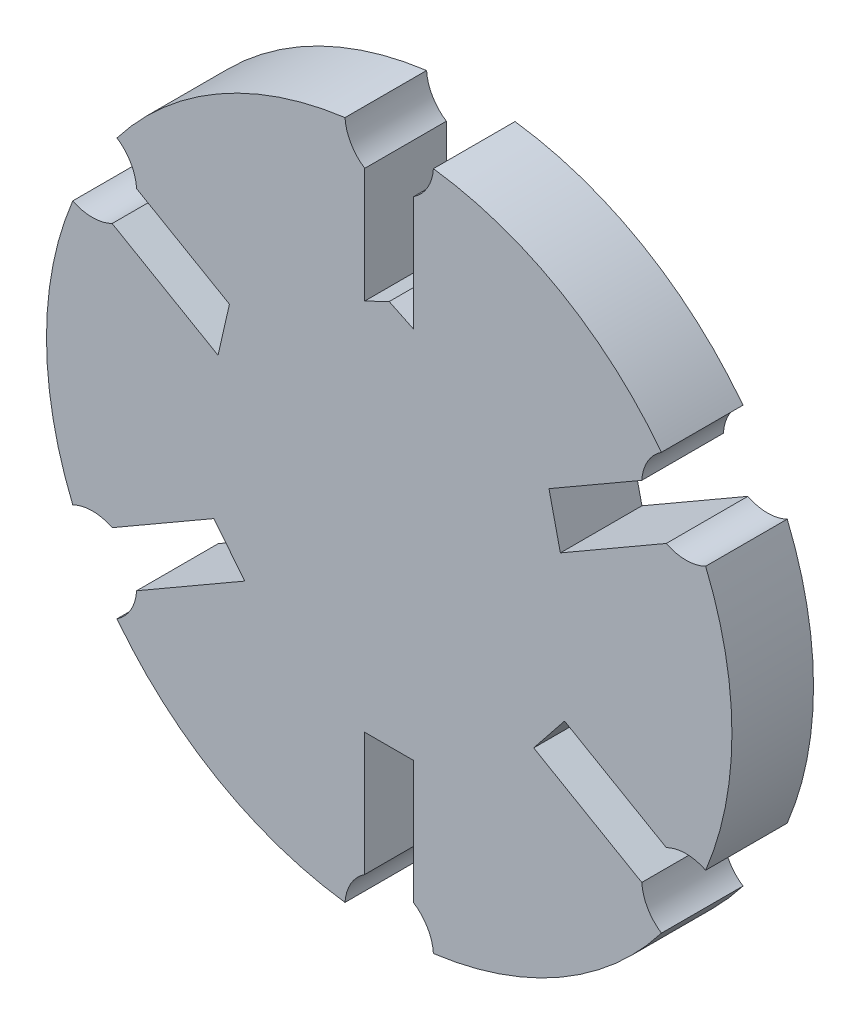
SolidWorks part; units mm, degrees
ref_plane "Front Plane" through (0, 0, 0) normal (0, 0, 1) x (1, 0, 0)
ref_plane "Top Plane" through (0, 0, 0) normal (0, 1, 0) x (1, 0, 0)
ref_plane "Right Plane" through (0, 0, 0) normal (1, 0, 0) x (0, 0, -1)
sketch "Sketch1" plane through (0, 0, 0) normal (0, 0, 1) x (1, 0, 0)
  line L1 (0, -1000) -> (0, -45) construction
  line L2 (19.4194, 15.4865) -> (0, 24.8383)
  line L3 (0, 24.8383) -> (-19.4194, 15.4865)
  line L4 (-19.4194, 15.4865) -> (-24.2156, -5.5271)
  line L5 (-24.2156, -5.5271) -> (-10.777, -22.3786)
  line L6 (-10.777, -22.3786) -> (10.777, -22.3786)
  line L7 (10.777, -22.3786) -> (24.2156, -5.5271)
  line L8 (24.2156, -5.5271) -> (19.4194, 15.4865)
  line L23 (22.9541, 0) -> (49000, 0) construction
  line L26 (20.9801, 8.6487) -> (33.9601, 16.1427)
  line L27 (19.5829, 14.7703) -> (30.9601, 21.3389)
  line L28 (3, 23.3936) -> (3, 37.4816)
  line L29 (-3, 23.3936) -> (-3, 37.4816)
  line L30 (-19.5829, 14.7703) -> (-30.9601, 21.3389)
  line L31 (-20.9801, 8.6487) -> (-33.9601, 16.1427)
  line L32 (-21.4909, -8.9437) -> (-33.9601, -16.1427)
  line L35 (-17.7055, -13.6864) -> (-30.9601, -21.3389)
  line L37 (17.7055, -13.6864) -> (30.9601, -21.3389)
  line L40 (21.4909, -8.9437) -> (33.9601, -16.1427)
  line L41 (-3, -22.3786) -> (-3, -37.4816)
  line L42 (3, -22.3786) -> (3, -37.4816)
  arc A0 (-5.4197, 41.6579) -> (-33.3669, 25.5225) centre (0, 0) ccw
  circle A1 centre (0, 0) radius 22.3786 construction
  circle A2 centre (0, 0) radius 45
  arc A3 (-5.4197, 41.6579) -> (5.4197, 41.6579) centre (0, 42.0089) ccw
  arc A4 (33.3669, 25.5225) -> (38.7866, 16.1353) centre (36.3808, 21.0045) ccw
  arc A5 (38.7866, -16.1353) -> (33.3669, -25.5225) centre (36.3808, -21.0045) ccw
  arc A6 (5.4197, -41.6579) -> (-5.4197, -41.6579) centre (0, -42.0089) ccw
  arc A7 (-33.3669, -25.5225) -> (-38.7866, -16.1353) centre (-36.3808, -21.0045) ccw
  arc A8 (-38.7866, 16.1353) -> (-33.3669, 25.5225) centre (-36.3808, 21.0045) ccw
  arc A9 (-38.7866, 16.1353) -> (-38.7866, -16.1353) centre (0, 0) ccw
  arc A10 (33.3669, 25.5225) -> (5.4197, 41.6579) centre (0, 0) ccw
  arc A11 (-33.3669, -25.5225) -> (-5.4197, -41.6579) centre (0, 0) ccw
  arc A12 (38.7866, -16.1353) -> (38.7866, 16.1353) centre (0, 0) ccw
  arc A13 (5.4197, -41.6579) -> (33.3669, -25.5225) centre (0, 0) ccw
  point P16 (0, 63.663)
  dimension "D1" = 42.0089
  dimension "D2" = 90
  dimension "D3" = 6
extrude "Boss-Extrude3" add sketch "Sketch1" along normal blind 10
